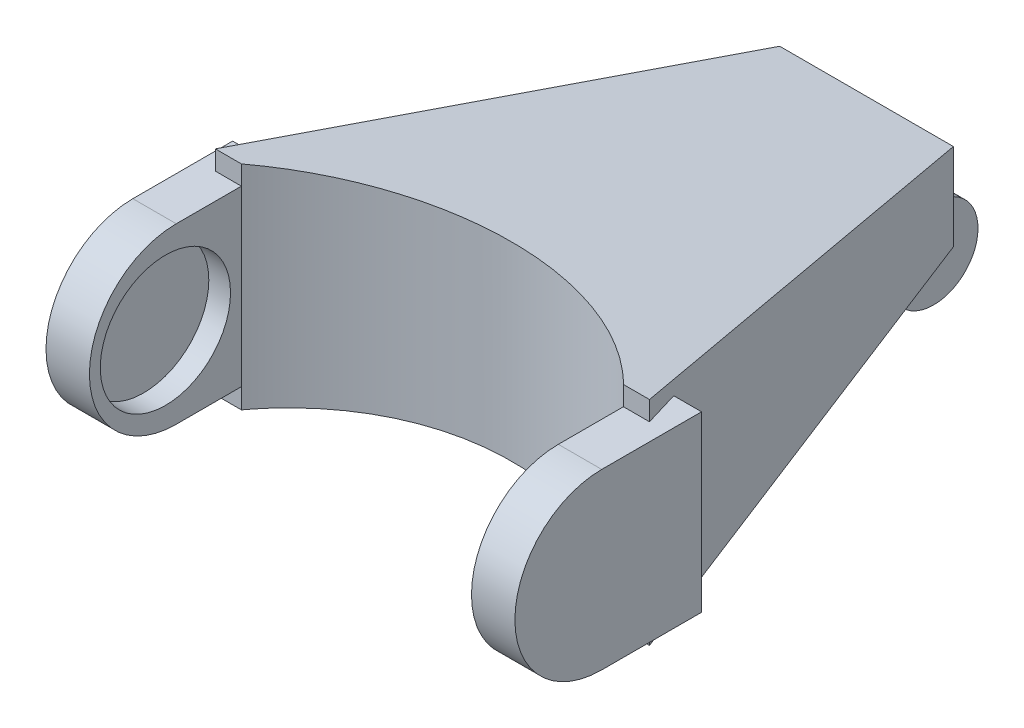
SolidWorks part; units mm, degrees
ref_plane "Front Plane" through (0, 0, 0) normal (0, 0, 1) x (1, 0, 0)
ref_plane "Top Plane" through (0, 0, 0) normal (0, 1, 0) x (1, 0, 0)
ref_plane "Right Plane" through (0, 0, 0) normal (1, 0, 0) x (0, 0, -1)
sketch "Sketch1" plane through (0, 0, 0) normal (0, 1, 0) x (1, 0, 0)
  line L4 (-10, 60) -> (10, 60)
  line L11 (-10, 60) -> (-25, 10)
  line L12 (10, 60) -> (25, 10)
  line L13 (-25, 10) -> (25, 10)
  point P0 (0, 0)
extrude "Boss-Extrude1" add sketch "Sketch1" along normal blind 30
ref_plane "Plane3" through (-25, 0, 0) normal (-1, 0, 0) x (0, -1, 0)
sketch "Sketch3" plane through (-25, 0, 0) normal (-1, 0, 0) x (0, -1, 0)
  line L0 (-30, -10) -> (0, -10) construction
  line L1 (0, -60) -> (0, -10) construction
  line L3 (-30, -60) -> (-30, -10) construction
  line L4 (-30, -10) -> (-27.2673, -10)
  line L5 (0, -60) -> (0, -10)
  line L7 (-30, -60) -> (-30, -10)
  line L8 (-15, -60) -> (-15, -10) construction
  line L9 (-30, -60) -> (-20, -60) construction
  line L10 (-30, -60) -> (-20, -60)
  line L11 (-27.2673, -10) -> (-20, -60)
  line L17 (-10, -60) -> (-2.7327, -10)
  line L18 (-2.7327, -10) -> (0, -10)
  line L19 (-10, -60) -> (0, -60) construction
  line L20 (-10, -60) -> (0, -60)
  dimension "D1" = 10
extrude "Cut-Extrude2" cut sketch "Sketch3" against normal blind 50
ref_plane "Plane8" through (0, 27.2673, 0) normal (0, 1, 0) x (-1, 0, 0)
sketch "Sketch10" plane through (0, 27.2673, 0) normal (0, 1, 0) x (-1, 0, 0)
  line L0 (-25, -10) -> (-22, -10) construction
  line L1 (-25, -10) -> (25, -10) construction
  line L2 (25, -10) -> (22, -10) construction
  line L3 (-22, -10) -> (22, -10)
  arc A0 (-22, -10) -> (22, -10) centre (0, 12) ccw
extrude "Cut-Extrude6" cut sketch "Sketch10" against normal blind 27
shell "Shell3" thickness 5
ref_plane "Plane5" through (-10, 0, 0) normal (1, 0, 0) x (0, -1, 0)
sketch "Sketch5" plane through (-10, 0, 0) normal (1, 0, 0) x (0, -1, 0)
  line L0 (-10, 60) -> (-2.7327, 10) construction
  line L1 (-20, 60) -> (-10, 60) construction
  line L2 (-10, 60) -> (-8.9608, 52.8503)
  line L3 (-15, 60) -> (-10, 60)
  arc A0 (-15, 60) -> (-8.9608, 52.8503) centre (-10.4322, 57.7329) cw
  dimension "D1" = 5.0995
extrude "Boss-Extrude3" add sketch "Sketch5" along normal blind 20
sketch "Sketch6" plane through (-25, 0, 0) normal (-1, 0, 0) x (0, -1, 0)
  line L1 (-25.0468, -9.9931) -> (-25.0468, -13.9931)
  line L2 (-25.0468, -2.5) -> (-5.0468, -2.5) construction
  line L4 (-25.0468, -2.5) -> (-25.0468, -9.9931)
  line L6 (-5.0468, -9.9931) -> (-5.0468, -2.5)
  line L7 (-25.0468, -13.9931) -> (-5.0468, -13.9931)
  line L9 (-5.0468, -13.9931) -> (-5.0468, -9.9931)
  arc A0 (-5.0468, -2.5) -> (-25.0468, -2.5) centre (-15.0468, -2.5) ccw
  point P0 (0, 0)
  dimension "D1" = 4
extrude "Boss-Extrude4" add sketch "Sketch6" against normal blind 3 and the other way blind 2
ref_plane "Plane6" through (0, 0, 0) normal (-1, 0, 0) x (0, 0, 1)
sketch "Sketch7" plane through (-22, 0, 0) normal (1, 0, 0) x (0, 0, -1)
  circle A2 centre (1.25, 15.0468) radius 7.5
extrude "Cut-Extrude3" cut sketch "Sketch7" against normal blind 2.5
mirror "Mirror2" about plane through (0, 0, 0) normal (-1, 0, 0) of "Cut-Extrude3", "Boss-Extrude4"
